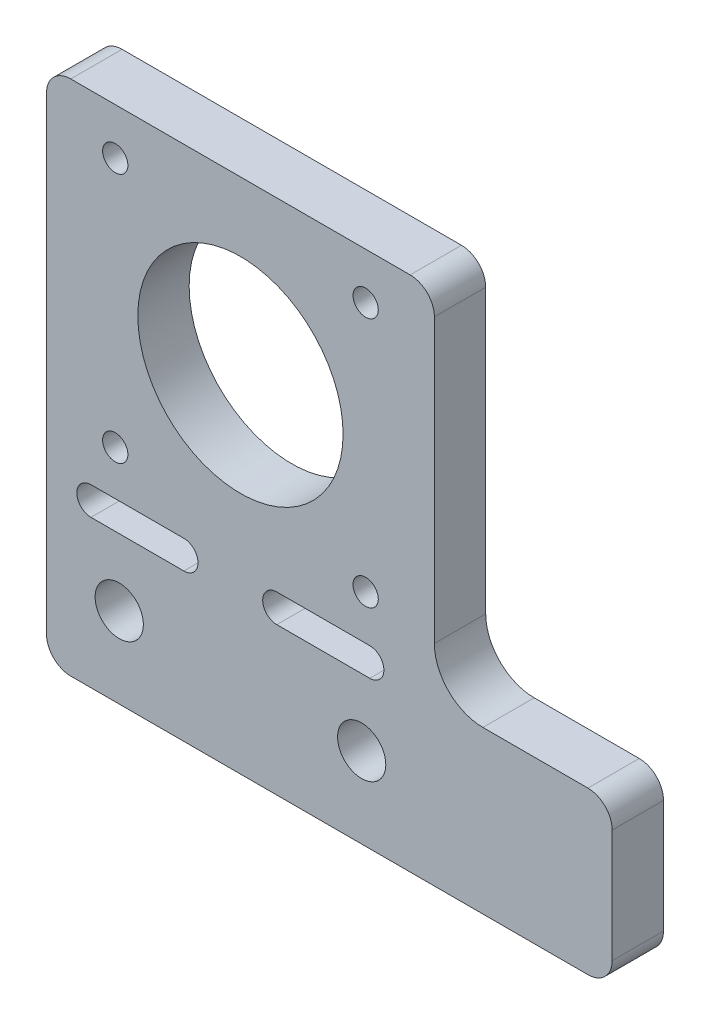
SolidWorks part; units mm, degrees
ref_plane "Front Plane" through (0, 0, 0) normal (0, 0, 1) x (1, 0, 0)
ref_plane "Top Plane" through (0, 0, 0) normal (0, 1, 0) x (1, 0, 0)
ref_plane "Right Plane" through (0, 0, 0) normal (1, 0, 0) x (0, 0, -1)
sketch "Sketch1" plane through (0, 0, 0) normal (0, 0, 1) x (1, 0, 0)
  line L22 (363.6837, 169.0339) -> (427.6837, 169.0339)
  line L27 (366.1837, 187.2995) -> (377.6837, 187.2995)
  line L28 (389.1837, 187.2995) -> (400.6837, 187.2995)
  line L29 (414.6837, 189.0339) -> (427.6837, 189.0339)
  line L33 (400.6837, 190.7995) -> (389.1837, 190.7995)
  line L34 (377.6837, 190.7995) -> (366.1837, 190.7995)
  line L53 (405.6837, 233.0339) -> (363.6837, 233.0339)
  line L82 (360.6837, 230.0339) -> (360.6837, 172.0339)
  line L89 (408.6837, 195.0339) -> (408.6837, 230.0339)
  line L92 (430.6837, 186.0339) -> (430.6837, 172.0339)
  arc A106 (408.6837, 195.0339) -> (414.6837, 189.0339) centre (414.6837, 195.0339) ccw
  arc A107 (430.6837, 186.0339) -> (427.6837, 189.0339) centre (427.6837, 186.0339) ccw
  arc A108 (360.6837, 172.0339) -> (363.6837, 169.0339) centre (363.6837, 172.0339) ccw
  arc A109 (427.6837, 169.0339) -> (430.6837, 172.0339) centre (427.6837, 172.0339) ccw
  circle A110 centre (369.6837, 179.0339) radius 2.9845
  circle A111 centre (399.6837, 179.0339) radius 2.9845
  arc A112 (400.6837, 187.2995) -> (400.6837, 190.7995) centre (400.6837, 189.0495) ccw
  arc A113 (389.1837, 190.7995) -> (389.1837, 187.2995) centre (389.1837, 189.0495) ccw
  arc A114 (377.6837, 187.2995) -> (377.6837, 190.7995) centre (377.6837, 189.0495) ccw
  arc A115 (366.1837, 190.7995) -> (366.1837, 187.2995) centre (366.1837, 189.0495) ccw
  circle A116 centre (369.1897, 196.3134) radius 1.5625
  circle A117 centre (400.1777, 196.3134) radius 1.5625
  circle A118 centre (384.6837, 211.8074) radius 12.7
  arc A119 (408.6837, 230.0339) -> (405.6837, 233.0339) centre (405.6837, 230.0339) ccw
  arc A120 (363.6837, 233.0339) -> (360.6837, 230.0339) centre (363.6837, 230.0339) ccw
  circle A121 centre (369.1897, 227.3014) radius 1.5625
  circle A122 centre (400.1777, 227.3014) radius 1.5625
extrude "Boss-Extrude1" add sketch "Sketch1" along normal blind 6.35
